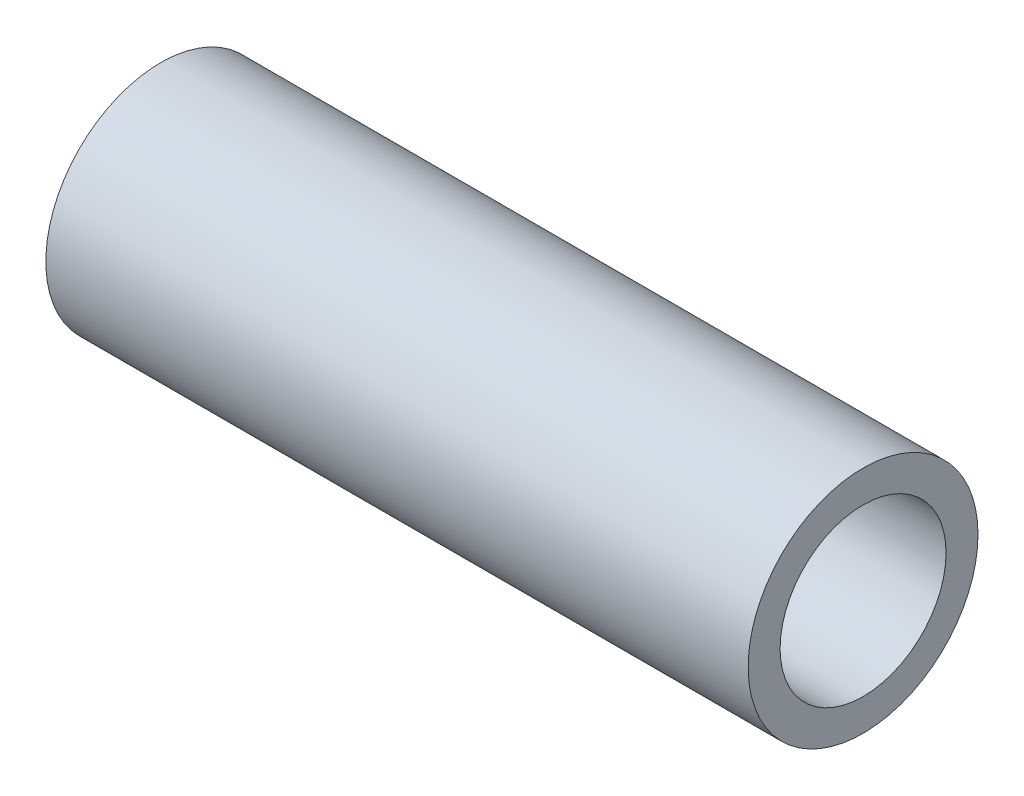
SolidWorks part; units mm, degrees
material "Cast Alloy Steel"
ref_plane "Front Plane" through (0, 0, 0) normal (0, 0, 1) x (1, 0, 0)
ref_plane "Top Plane" through (0, 0, 0) normal (0, 1, 0) x (1, 0, 0)
ref_plane "Right Plane" through (0, 0, 0) normal (1, 0, 0) x (0, 0, -1)
sketch "Sketch2" plane through (0, 0, 0) normal (1, 0, 0) x (0, 0, -1)
  circle A0 centre (0, 0) radius 6.5
  circle A1 centre (0, 0) radius 9
  dimension "D1" = 18
  dimension "D2" = 13
extrude "Boss-Extrude1" add sketch "Sketch2" along normal mid plane 55
